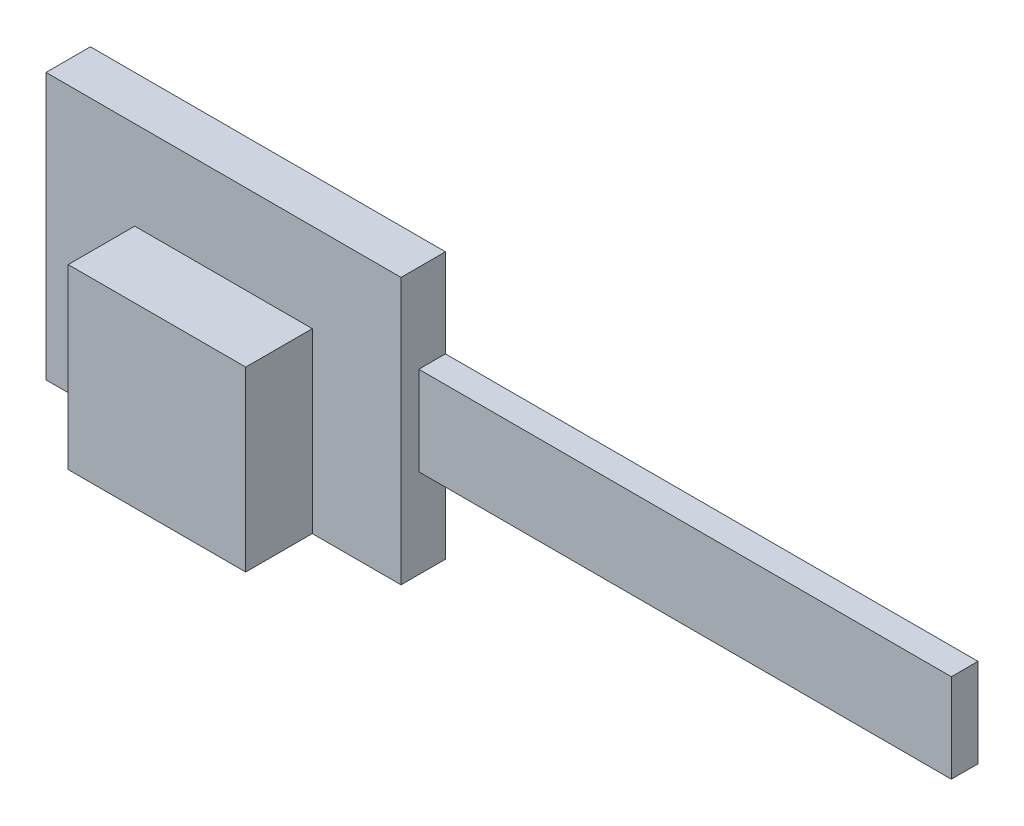
SolidWorks part; units mm, degrees
ref_plane "Front Plane" through (0, 0, 0) normal (0, 0, 1) x (1, 0, 0)
ref_plane "Top Plane" through (0, 0, 0) normal (0, 1, 0) x (1, 0, 0)
ref_plane "Right Plane" through (0, 0, 0) normal (1, 0, 0) x (0, 0, -1)
sketch "Sketch1" plane through (0, 0, 0) normal (0, 0, 1) x (1, 0, 0)
  line L1 (-4, 3) -> (4, 3)
  line L2 (-4, 3) -> (-4, -3)
  line L3 (-4, -3) -> (4, -3)
  line L4 (4, 3) -> (4, -3)
  point P4 (0, 3)
  point P6 (4, 0)
  dimension "D1" = 8
  dimension "D2" = 6
extrude "Boss-Extrude1" add sketch "Sketch1" along normal blind 1
sketch "Sketch2" plane through (0, 0, 1) normal (0, 0, 1) x (1, 0, 0)
  line L0 (-4, -3) -> (4, -3) construction
  line L1 (-2, 1) -> (2, 1)
  line L2 (-2, 1) -> (-2, -3)
  line L3 (-2, -3) -> (2, -3)
  line L4 (2, 1) -> (2, -3)
  line L5 (4, 3) -> (-4, 3) construction
  point P6 (0, 3)
  point P9 (0, 1)
  dimension "D1" = 4
  dimension "D2" = 4
extrude "Boss-Extrude2" add sketch "Sketch2" along normal blind 1.5
sketch "Sketch3" plane through (0, 0, 0) normal (0, 0, -1) x (-1, 0, 0)
  line L0 (-4, -3) -> (-4, 3) construction
  line L1 (-4, 1.0076) -> (-16, 1.0076)
  line L2 (-4, 1.0076) -> (-4, -0.9924)
  line L3 (-4, -0.9924) -> (-16, -0.9924)
  line L4 (-16, 1.0076) -> (-16, -0.9924)
  dimension "D1" = 2
  dimension "D2" = 12
extrude "Boss-Extrude3" add sketch "Sketch3" against normal blind 0.6 separate body
